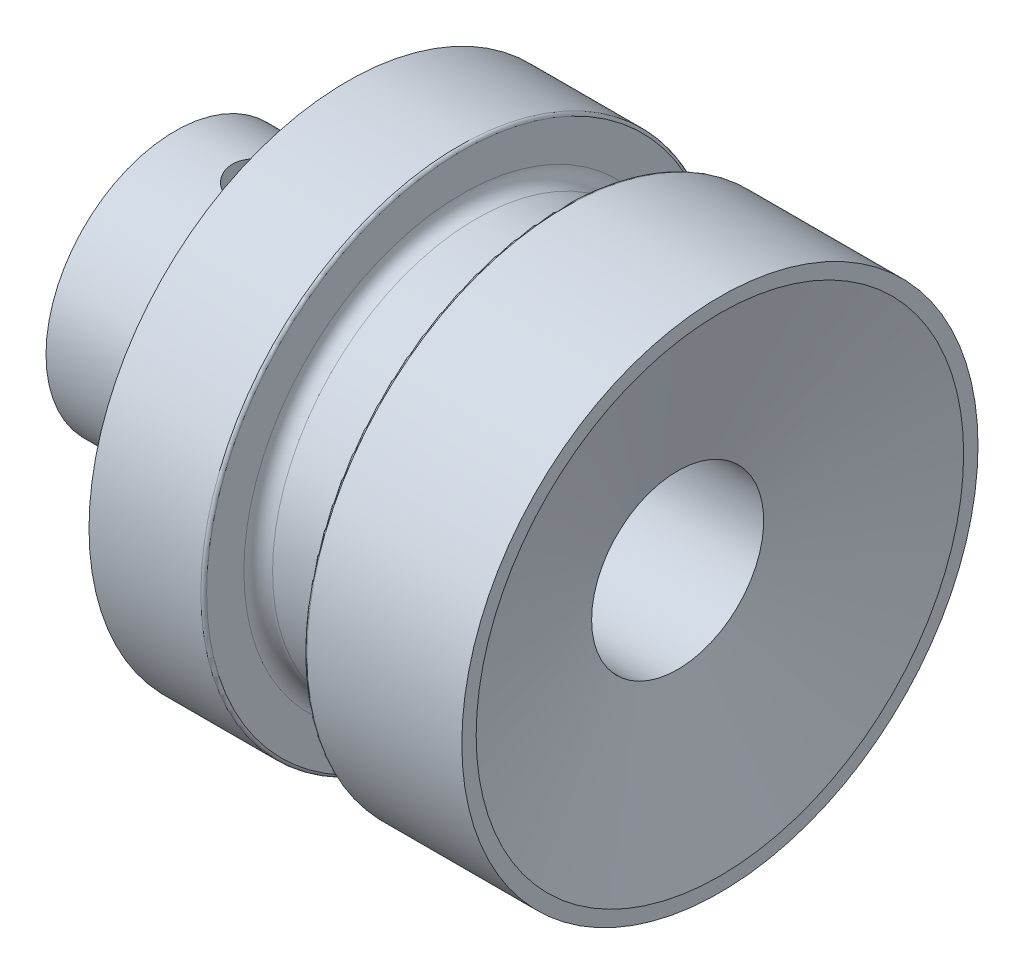
SolidWorks part; units mm, degrees
material "ПТФЭ (общий)"
ref_plane "Спереди" through (0, 0, 0) normal (0, 0, 1) x (1, 0, 0)
ref_plane "Сверху" through (0, 0, 0) normal (0, 1, 0) x (1, 0, 0)
ref_plane "Справа" through (0, 0, 0) normal (1, 0, 0) x (0, 0, -1)
sketch "Эскиз1" plane through (0, 0, 0) normal (0, 0, 1) x (1, 0, 0)
  line L0 (0, 0) -> (109.2795, 0) construction
  line L1 (0, 3) -> (0, 4.5)
  line L2 (0, 4.5) -> (6, 4.5)
  line L3 (6, 4.5) -> (6, 9)
  line L4 (6, 9) -> (9.9, 9)
  line L5 (10, 8.9) -> (10, 7.6)
  line L6 (10.5, 7.1) -> (13, 7.1)
  line L7 (13.5, 7.6) -> (13.5, 8.9)
  line L8 (13.6, 9) -> (19, 9)
  line L9 (19, 9) -> (19, 8.5)
  line L10 (19, 8.5) -> (17.5263, 3)
  line L11 (17.5263, 3) -> (0, 3)
  arc A0 (13, 7.1) -> (13.5, 7.6) centre (13, 7.6) ccw
  arc A1 (10, 7.6) -> (10.5, 7.1) centre (10.5, 7.6) ccw
  arc A2 (13.5, 8.9) -> (13.6, 9) centre (13.6, 8.9) cw
  arc A3 (9.9, 9) -> (10, 8.9) centre (9.9, 8.9) cw
  point P16 (13.5, 7.1)
  point P19 (10, 7.1)
  dimension "D11" = 0.5
  dimension "D12" = 0.1
  dimension "D1" = 6
  dimension "D2" = 9
  dimension "D3" = 17
  dimension "D4" = 18
  dimension "D5" = 14.2
  dimension "D6" = 3.5
  dimension "D7" = 75
  dimension "D8" = 7.5
  dimension "D9" = 6
  dimension "D10" = 19
revolve "Повернуть1" add sketch "Эскиз1" angle 360 about L0
sketch "Эскиз2" plane through (0, 0, 0) normal (0, 1, 0) x (1, 0, 0)
  line L0 (6, 9) -> (6, -9) construction
  circle A0 centre (3, 0) radius 1
  dimension "D1" = 2
  dimension "D2" = 3
extrude "Вырез-Вытянуть1" cut sketch "Эскиз2" against normal through all and the other way through all
